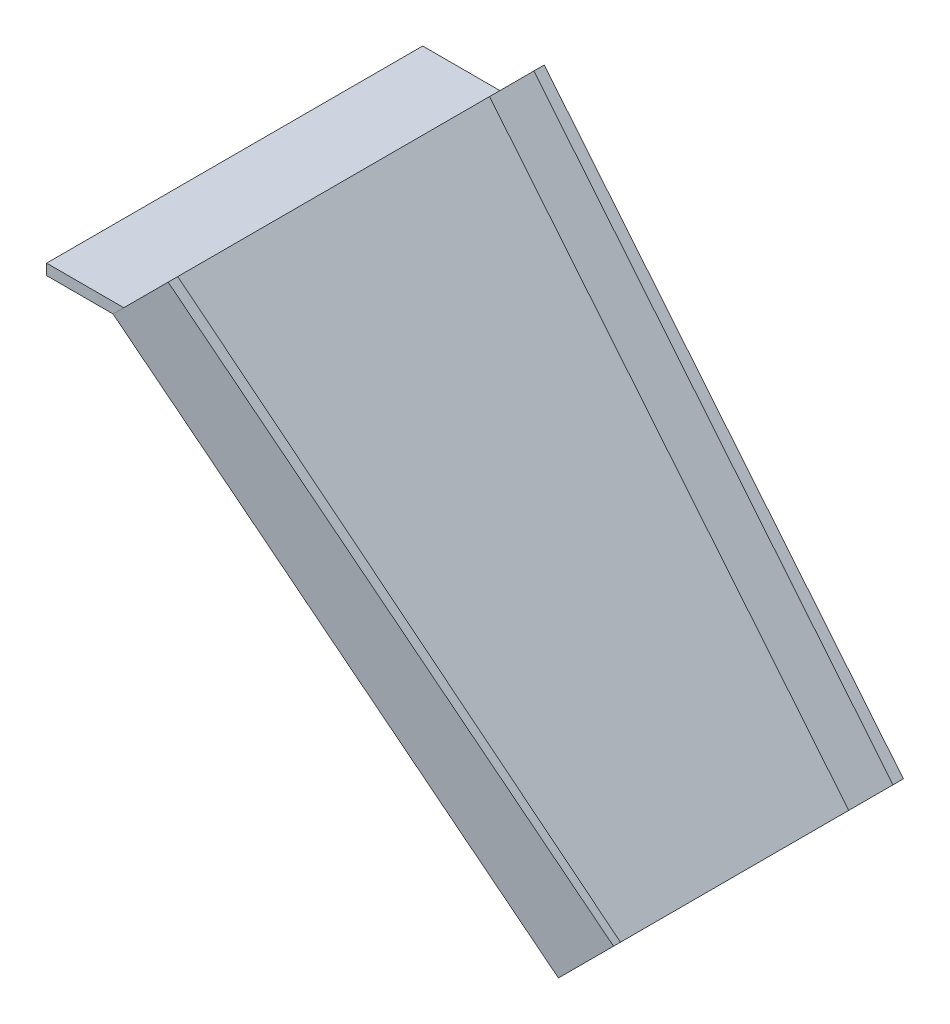
SolidWorks part; units mm, degrees
ref_plane "Front Plane" through (0, 0, 0) normal (0, 0, 1) x (1, 0, 0)
ref_plane "Top Plane" through (0, 0, 0) normal (0, 1, 0) x (1, 0, 0)
ref_plane "Right Plane" through (0, 0, 0) normal (1, 0, 0) x (0, 0, -1)
sketch "Sketch1" plane through (0, 0, 0) normal (0, 0, 1) x (1, 0, 0)
  line L0 (-31.8198, 31.8198) -> (31.8198, -31.8198)
  line L1 (-31.8198, 31.8198) -> (-44.1372, 31.8198)
  line L2 (-44.1372, 31.8198) -> (-44.1372, 30.0978)
  line L3 (-44.1372, 30.0978) -> (-33.5418, 30.0978)
  line L4 (-33.5418, 30.0978) -> (30.0978, -33.5418)
  line L5 (30.0978, -33.5418) -> (31.8198, -31.8198)
  point P4 (0, 0)
  dimension "D1" = 90
  dimension "D2" = 12.3174
  dimension "D3" = 2.4353
extrude "Boss-Extrude1" add sketch "Sketch1" along normal blind 60
sketch "Sketch6" plane through (0, 0, 0) normal (0.7071, 0.7071, 0) x (0.7071, -0.7071, 0)
  line L0 (-45, -60) -> (45, -52.5774)
  line L1 (45, -60) -> (45, 0) construction
extrude "Cut-Extrude-Thin3" cut sketch "Sketch6" against normal through all and the other way through all thin
sketch "Sketch7" plane through (0, 0, 0) normal (0.7071, 0.7071, 0) x (0.7071, -0.7071, 0)
  line L0 (-45, 0) -> (45, -6.3379)
  line L1 (45, -52.5774) -> (45, 0) construction
extrude "Cut-Extrude-Thin4" cut sketch "Sketch7" against normal through all and the other way through all thin thin type one direction reverse wall 500
sketch "Sketch8" plane through (0, 0, 0) normal (0.7071, 0.7071, 0) x (0, 0, -1)
  line L0 (-60, 45) -> (-58.4672, 45)
  line L1 (-60, 45) -> (0, 45) construction
  line L2 (-58.4672, 45) -> (-51.4731, -45)
  line L3 (-52.5774, -45) -> (-6.3379, -45) construction
  line L4 (-51.4731, -45) -> (-52.5774, -45)
  line L9 (-52.5774, -45) -> (-6.3379, -45)
  line L10 (-6.3379, -45) -> (0, 45)
  line L11 (0, 45) -> (-60, 45)
  line L12 (-60, 45) -> (-52.5774, -45)
  line L16 (-60, 45) -> (-52.5774, -45)
  dimension "D1" = 0
extrude "Boss-Extrude4" add sketch "Sketch8" along normal blind 10
sketch "Sketch9" plane through (0, 0, 0) normal (0.7071, 0.7071, 0) x (0, 0, -1)
  line L0 (0, 45) -> (-1.6536, 45)
  line L1 (-58.4672, 45) -> (0, 45) construction
  line L2 (-1.6536, 45) -> (-7.9915, -45)
  line L3 (-51.4731, -45) -> (-6.3379, -45) construction
  line L4 (-7.9915, -45) -> (-6.3379, -45)
  line L9 (-58.4672, 45) -> (-51.4731, -45)
  line L10 (-51.4731, -45) -> (-6.3379, -45)
  line L11 (-6.3379, -45) -> (0, 45)
  line L12 (0, 45) -> (-58.4672, 45)
  line L13 (-58.4672, 45) -> (-51.4731, -45)
  line L14 (-51.4731, -45) -> (-6.3379, -45)
  line L16 (0, 45) -> (-58.4672, 45)
  line M6 (-51.4731, -45) -> (-6.3379, -45)
  line M7 (-6.3379, -45) -> (0, 45)
  line M8 (0, 45) -> (-58.4672, 45)
  dimension "D1" = 0
extrude "Boss-Extrude5" add sketch "Sketch9" along normal blind 10 contours L2 M8 M6 M7
